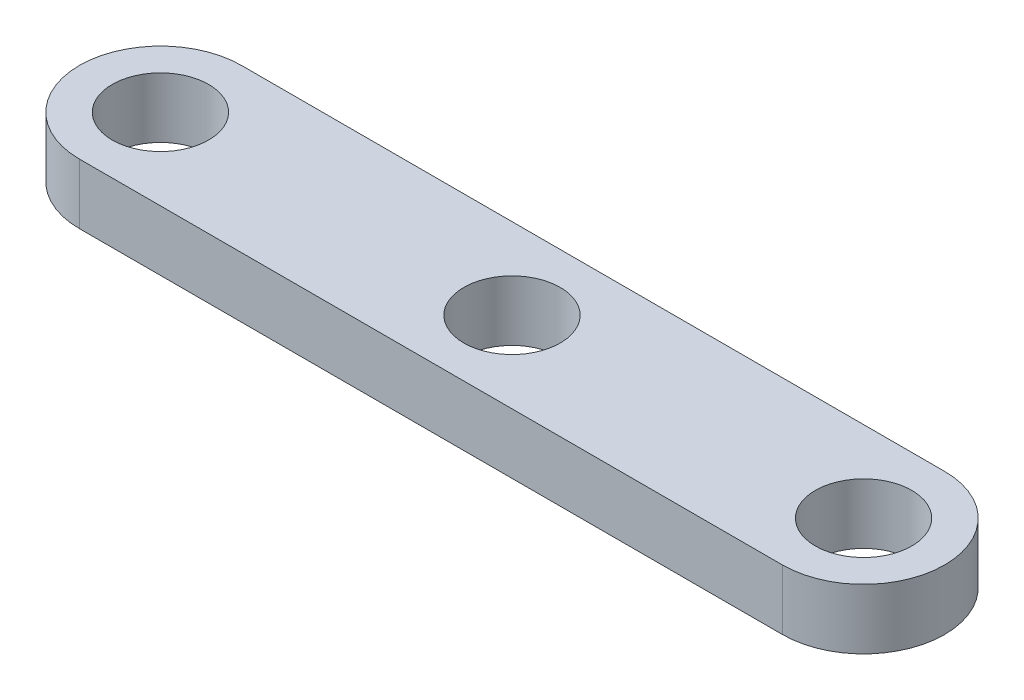
SolidWorks part; units mm, degrees
ref_plane "Front Plane" through (0, 0, 0) normal (0, 0, 1) x (1, 0, 0)
ref_plane "Top Plane" through (0, 0, 0) normal (0, 1, 0) x (1, 0, 0)
ref_plane "Right Plane" through (0, 0, 0) normal (1, 0, 0) x (0, 0, -1)
sketch "Sketch1" plane through (0, 0, 0) normal (0, 1, 0) x (1, 0, 0)
  line L0 (-17.5, 0) -> (17.5, 0) construction
  line L7 (-17.5, 4.035) -> (17.5, 4.035)
  line L8 (-17.5, -4.035) -> (17.5, -4.035)
  circle A0 centre (-17.5, 0) radius 2.4
  circle A1 centre (17.5, 0) radius 2.4
  circle A5 centre (0, 0) radius 2.4
  arc A6 (-17.5, 4.035) -> (-17.5, -4.035) centre (-17.5, 0) ccw
  arc A7 (17.5, -4.035) -> (17.5, 4.035) centre (17.5, 0) ccw
  point P0 (0, 0)
  point P16 (0, 0)
  dimension "D3" = 4.8
  dimension "D4" = 4.8
  dimension "D9" = 4.8
  dimension "D10" = 8.07
extrude "Boss-Extrude2" add sketch "Sketch1" along normal blind 3
